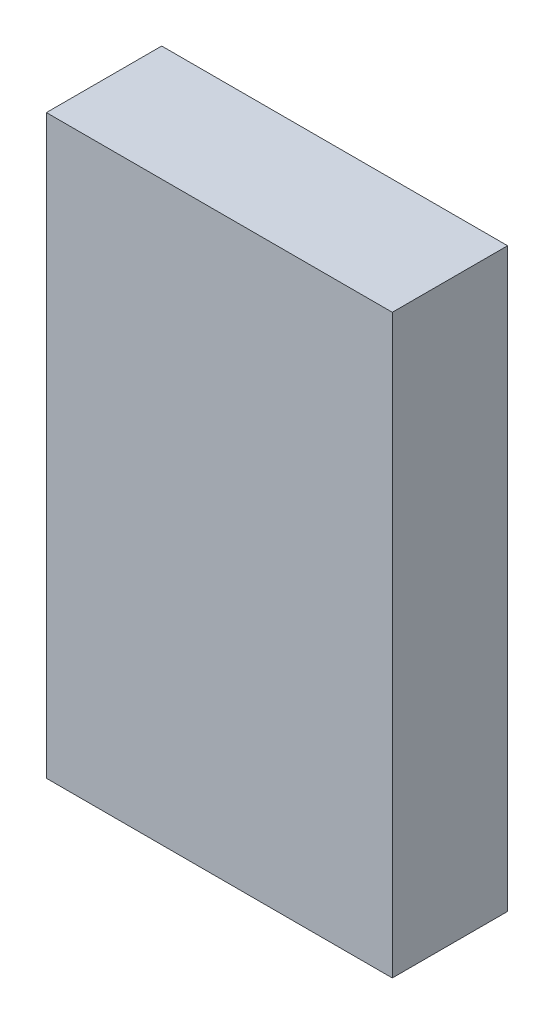
SolidWorks part; units mm, degrees
material "Полиуретан (11671)"
ref_plane "Спереди" through (0, 0, 0) normal (0, 0, 1) x (1, 0, 0)
ref_plane "Сверху" through (0, 0, 0) normal (0, 1, 0) x (1, 0, 0)
ref_plane "Справа" through (0, 0, 0) normal (1, 0, 0) x (0, 0, -1)
sketch "Эскиз1" plane through (0, 0, 0) normal (0, 0, 1) x (1, 0, 0)
  line L1 (-1.5, -2.5) -> (1.5, -2.5)
  line L2 (-1.5, -2.5) -> (-1.5, 2.5)
  line L3 (-1.5, 2.5) -> (1.5, 2.5)
  line L4 (1.5, -2.5) -> (1.5, 2.5)
  line L5 (-1.5, -2.5) -> (1.5, 2.5) construction
  line L6 (-1.5, 2.5) -> (1.5, -2.5) construction
  point P0 (0, 0)
  dimension "D1" = 5
  dimension "D2" = 3
extrude "Бобышка-Вытянуть1" add sketch "Эскиз1" along normal blind 1
